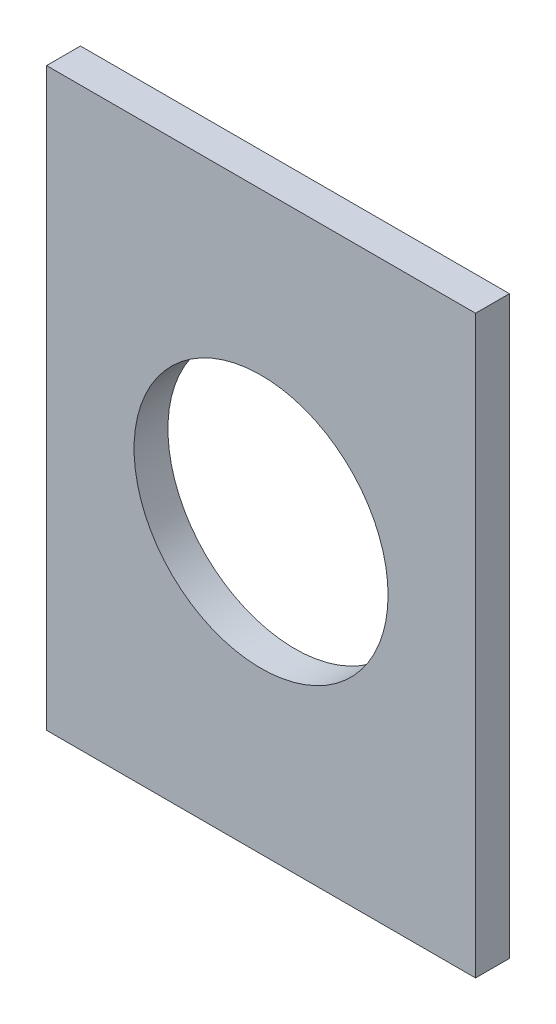
SolidWorks part; units mm, degrees
ref_plane "Plan1" through (0, 0, 0) normal (0, 0, 1) x (1, 0, 0)
ref_plane "Plan2" through (0, 0, 0) normal (0, 1, 0) x (1, 0, 0)
ref_plane "Plan3" through (0, 0, 0) normal (1, 0, 0) x (0, 0, -1)
sketch "Esquisse1" plane through (0, 0, 0) normal (0, 0, 1) x (1, 0, 0)
  line L0 (-19, 25.5) -> (19, 25.5)
  line L1 (-19, 25.5) -> (-19, -25.5)
  line L2 (19, -25.5) -> (-19, -25.5)
  line L3 (19, -25.5) -> (19, 25.5)
  circle A0 centre (0, 0) radius 11.25
  dimension "D5" = 22.5
  dimension "D1" = 51
  dimension "D2" = 38
  dimension "D3" = 19
  dimension "D4" = 25.5
extrude "Base-Extrusion" add sketch "Esquisse1" along normal blind 3
